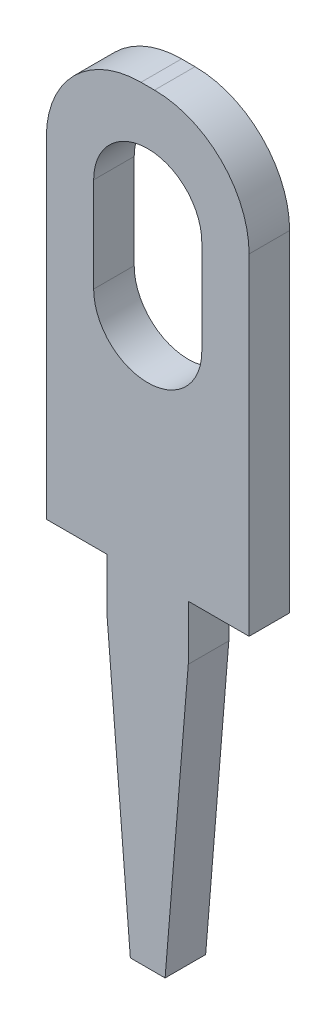
SolidWorks part; units mm, degrees
ref_plane "Piano frontale" through (0, 0, 0) normal (0, 0, 1) x (1, 0, 0)
ref_plane "Piano superiore" through (0, 0, 0) normal (0, 1, 0) x (1, 0, 0)
ref_plane "Piano destro" through (0, 0, 0) normal (1, 0, 0) x (0, 0, -1)
sketch "Schizzo1" plane through (0, 0, 0) normal (0, 0, 1) x (1, 0, 0)
  line L0 (0, 0) -> (0, 10.3276) construction
  line L1 (-1.5, 0) -> (-0.6, 0)
  line L2 (-1.5, 0) -> (-1.5, 4.9)
  line L3 (-0.1, 6.3) -> (0.1, 6.3)
  line L4 (1.5, 0) -> (1.5, 4.9)
  line L5 (-0.2571, -5) -> (-0.6, -0.8082)
  line L6 (-0.6, 0) -> (-0.6, -0.8082)
  line L7 (-0.2571, -5) -> (0.2571, -5)
  line L8 (0.6, 0) -> (0.6, -0.8082)
  line L9 (0, 4.7) -> (0, 3.3) construction
  line L10 (0.8, 4.7) -> (0.8, 3.3)
  line L11 (-0.8, 4.7) -> (-0.8, 3.3)
  line L12 (0.6, 0) -> (1.5, 0)
  line L13 (0.2571, -5) -> (0.6, -0.8082)
  arc A0 (0.1, 6.3) -> (1.5, 4.9) centre (0.1, 4.9) cw
  arc A1 (-1.5, 4.9) -> (-0.1, 6.3) centre (-0.1, 4.9) cw
  arc A2 (0.8, 4.7) -> (-0.8, 4.7) centre (0, 4.7) ccw
  arc A3 (-0.8, 3.3) -> (0.8, 3.3) centre (0, 3.3) ccw
  point P14 (1.5, 6.3)
  point P17 (-1.5, 6.3)
  point P20 (0, 4)
  dimension "D5" = 1.4
  dimension "D7" = 1.6
  dimension "D1" = 3
  dimension "D2" = 6.3
  dimension "D3" = 5
  dimension "D6" = 4
  dimension "D8" = 1.4
extrude "Estrusione-Estrusione1" add sketch "Schizzo1" along normal blind 0.6
